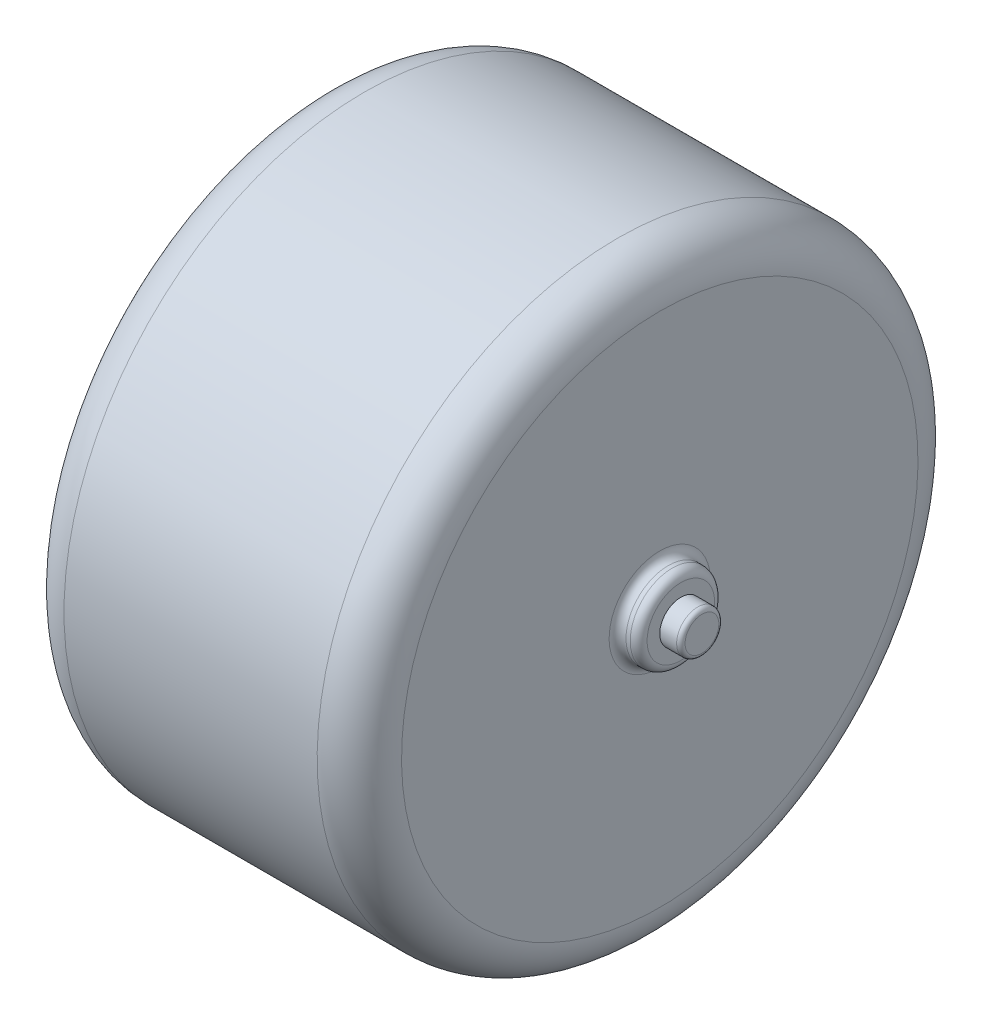
SolidWorks part; units mm, degrees
ref_plane "Front" through (0, 0, 0) normal (0, 0, 1) x (1, 0, 0)
ref_plane "Top" through (0, 0, 0) normal (0, 1, 0) x (1, 0, 0)
ref_plane "Right" through (0, 0, 0) normal (1, 0, 0) x (0, 0, -1)
sketch "Sketch1" plane through (0, 0, 0) normal (0, 0, 1) x (1, 0, 0)
  line L0 (0, 0) -> (0, 6.35)
  line L1 (0, 6.35) -> (25.4, 6.35)
  line L2 (25.4, 6.35) -> (25.4, 12.7)
  line L3 (25.4, 12.7) -> (31.75, 12.7)
  line L4 (31.75, 12.7) -> (31.75, 90.4301)
  line L5 (31.75, 90.4301) -> (133.35, 90.4301)
  line L6 (133.35, 90.4301) -> (133.35, 12.7)
  line L7 (133.35, 12.7) -> (139.7, 12.7)
  line L8 (139.7, 12.7) -> (139.7, 6.35)
  line L9 (139.7, 6.35) -> (146.05, 6.35)
  line L10 (146.05, 6.35) -> (146.05, 0)
  line L11 (146.05, 0) -> (0, 0)
revolve "Revolve1" add sketch "Sketch1" angle 360 about L11
fillet "Fillet1" radius 12.7 2 edges at (133.35, 90.4301, 0) (31.75, 90.4301, 0)
fillet "Fillet2" radius 2.54 4 edges at (25.4, 12.7, 0) (31.75, 12.7, 0) (133.35, 12.7, 0) (139.7, 12.7, 0)
fillet "Fillet3" radius 1.27 2 edges at (146.05, 6.35, 0) (0, 6.35, 0)
sketch "Sketch2" plane through (31.75, 0, 0) normal (-1, 0, 0) x (0, 0, 1)
  circle A0 centre (0, 0) radius 50.8 construction
hole_wizard "3/8-16 Tapped Hole1" positions "3DSketch1" profile "Sketch3" tap size "3/8-16" standard "Superior"
sketch3d "3DSketch1"
  point P0 (31.75, 63.5, 0)
sketch "Sketch3" plane through (31.75, 63.5, 0) normal (0, 1, 0) x (0, 0, 1)
  line L0 (0, 0) -> (0, 29.3722)
  line L1 (0, 29.3722) -> (3.9687, 26.9875)
  line L2 (3.9687, 26.9875) -> (3.9687, 19.05)
  line L3 (3.9687, 19.05) -> (4.7625, 19.05)
  line L4 (4.7625, 19.05) -> (4.7625, 0)
  line L5 (4.7625, 0) -> (0, 0)
  line L10 (0, 29.3722) -> (-3.9688, 26.9875) construction
  line L11 (0, -6.35) -> (0, 107.95) construction
  dimension "Tap Drill Dia." = 7.9375
  dimension "Tap Drill Depth" = 26.9875
  dimension "Thread Major Dia." = 9.525
  dimension "Thread Depth" = 19.05
  dimension "Drill Angle" = 118
pattern_circular "CirPattern1" count 3 over 360 about axis through (0, 0, 0) along (1, 0, 0) of "3/8-16 Tapped Hole1"
